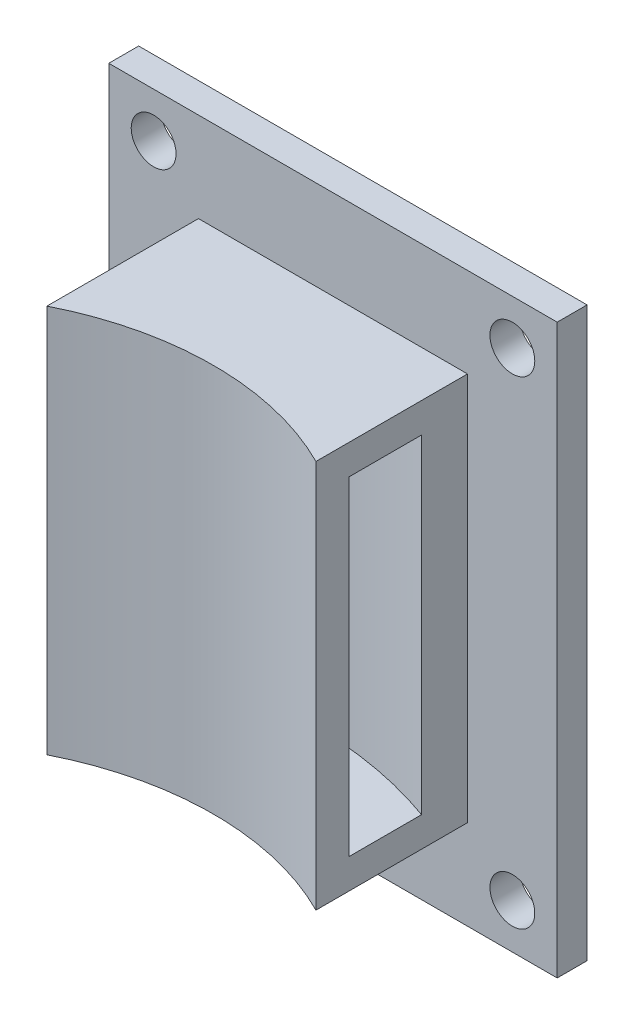
SolidWorks part; units mm, degrees
ref_plane "前视基准面" through (0, 0, 0) normal (0, 0, 1) x (1, 0, 0)
ref_plane "上视基准面" through (0, 0, 0) normal (0, 1, 0) x (1, 0, 0)
ref_plane "右视基准面" through (0, 0, 0) normal (1, 0, 0) x (0, 0, -1)
sketch "草图1" plane through (0, 0, 0) normal (0, 1, 0) x (1, 0, 0)
  line L0 (-9, 30) -> (-9, 24.9249)
  line L1 (0, -1000) -> (0, 49000) construction
  line L2 (9, 30) -> (9, 24.9249)
  line L3 (-9, 30) -> (9, 30)
  line L4 (-9, 20.0749) -> (-9, 17.8606)
  line L5 (9, 20.0749) -> (9, 17.8606)
  arc A0 (9, 17.8606) -> (-9, 17.8606) centre (0, 0) ccw
  arc A1 (9, 20.0749) -> (-9, 20.0749) centre (0, 0) ccw
  arc A2 (9, 24.9249) -> (-9, 24.9249) centre (0, 0) ccw
  circle A3 centre (0, 0) radius 26.5 construction
  circle A4 centre (0, 0) radius 22 construction
  circle A5 centre (0, 0) radius 20 construction
  point P17 (0, 0)
  dimension "D1" = 40
  dimension "D4" = 18
  dimension "D5" = 30
  dimension "D2" = 2
  dimension "D3" = 4.5
extrude "凸台-拉伸1" add sketch "草图1" along normal mid plane 22
sketch "草图2" plane through (0, 11, 0) normal (0, 1, 0) x (1, 0, 0)
  line L0 (-9, 30) -> (-9, 17.8606)
  line L2 (9, 17.8606) -> (9, 20.0749)
  line L3 (9, 30) -> (-9, 30)
  line L4 (-9, 30) -> (-9, 24.9249)
  line L5 (9, 24.9249) -> (9, 30)
  line L6 (9, 30) -> (-9, 30)
  line L9 (-9, 20.0749) -> (-9, 17.8606)
  line L12 (9, 17.8606) -> (9, 30)
  arc A1 (9, 24.9249) -> (-9, 24.9249) centre (0, 0) ccw
  arc A4 (9, 17.8606) -> (-9, 17.8606) centre (0, 0) ccw
  arc A5 (9, 20.0749) -> (-9, 20.0749) centre (0, 0) ccw
  arc A6 (9, 17.8606) -> (-9, 17.8606) centre (0, 0) ccw
  dimension "D1" = 0
  dimension "D2" = 0
extrude "凸台-拉伸2" add sketch "草图2" along normal blind 2
mirror "镜向1" about plane through (0, 0, 0) normal (0, 1, 0) of "凸台-拉伸2"
sketch "草图5" plane through (0, 0, -30) normal (0, 0, -1) x (-1, 0, 0)
  line L8 (-9, 13) -> (-9, -13)
  line L9 (-9, -13) -> (9, -13)
  line L10 (9, -13) -> (9, 13)
  line L11 (9, 13) -> (-9, 13)
  line L12 (-9, 13) -> (-9, -13)
  line L13 (-9, -13) -> (9, -13)
  line L14 (9, -13) -> (9, 13)
  line L15 (9, 13) -> (-9, 13)
  line L20 (-15, 19) -> (-15, -19)
  line L21 (-15, -19) -> (15, -19)
  line L22 (15, -19) -> (15, 19)
  line L23 (15, 19) -> (-15, 19)
  line L24 (-15, 19) -> (-15, -19)
  line L25 (-15, -19) -> (15, -19)
  line L26 (15, -19) -> (15, 19)
  line L27 (15, 19) -> (-15, 19)
  dimension "D1" = 0
  dimension "D2" = 6
extrude "凸台-拉伸3" add sketch "草图5" against normal blind 2
sketch "草图6" plane through (0, 0, -28) normal (0, 0, 1) x (1, 0, 0)
  line L0 (15, 19) -> (15, -19) construction
  line L1 (-15, 19) -> (15, 19) construction
  line L2 (0, 19) -> (0, -19) construction
  line L3 (15, -19) -> (-15, -19) construction
  line L4 (-15, 0) -> (15, 0) construction
  line L5 (-15, -19) -> (-15, 19) construction
  circle A0 centre (12, 16) radius 1.5
  circle A1 centre (-12, 16) radius 1.5
  circle A2 centre (12, -16) radius 1.5
  circle A3 centre (-12, -16) radius 1.5
  dimension "D1" = 3
  dimension "D2" = 3
  dimension "D3" = 3
extrude "切除-拉伸1" cut sketch "草图6" against normal through all
